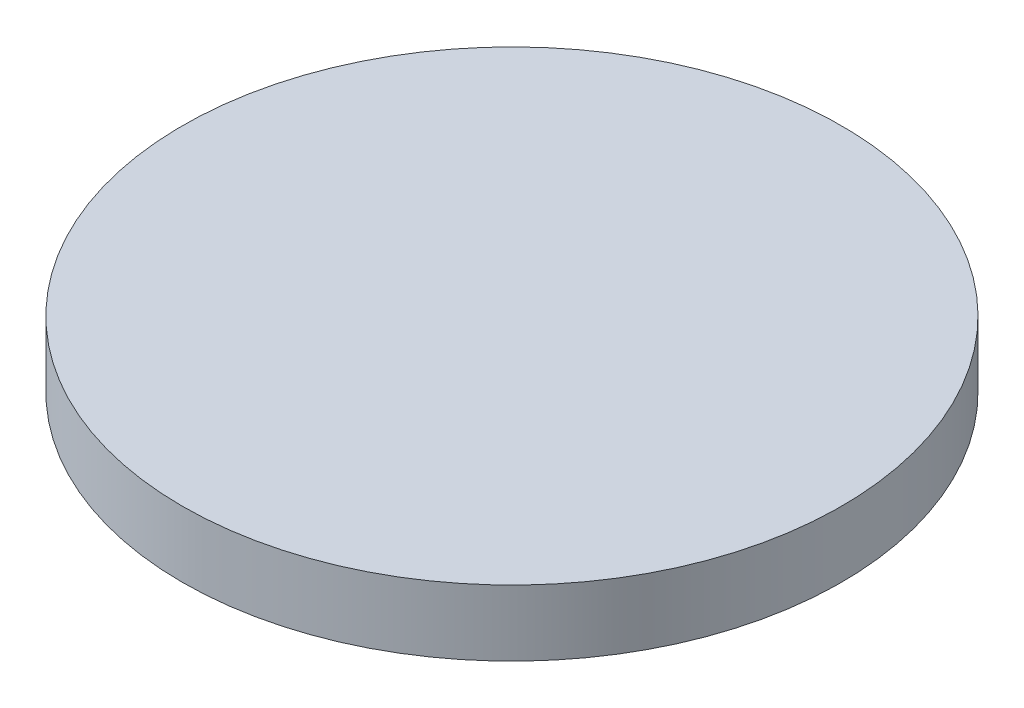
SolidWorks part; units mm, degrees
ref_plane "Front Plane" through (0, 0, 0) normal (0, 0, 1) x (1, 0, 0)
ref_plane "Top Plane" through (0, 0, 0) normal (0, 1, 0) x (1, 0, 0)
ref_plane "Right Plane" through (0, 0, 0) normal (1, 0, 0) x (0, 0, -1)
sketch "Sketch1" plane through (0, 0, 0) normal (0, 1, 0) x (1, 0, 0)
  circle A0 centre (0, 0) radius 10
  dimension "D1" = 20
extrude "Boss-Extrude1" add sketch "Sketch1" along normal blind 2
sketch "Sketch2" plane through (0, 0, 0) normal (0, -1, 0) x (1, 0, 0)
  circle A0 centre (0, 0) radius 4.9
  dimension "D1" = 9.8
extrude "Boss-Extrude2" add sketch "Sketch2" along normal blind 2.9
